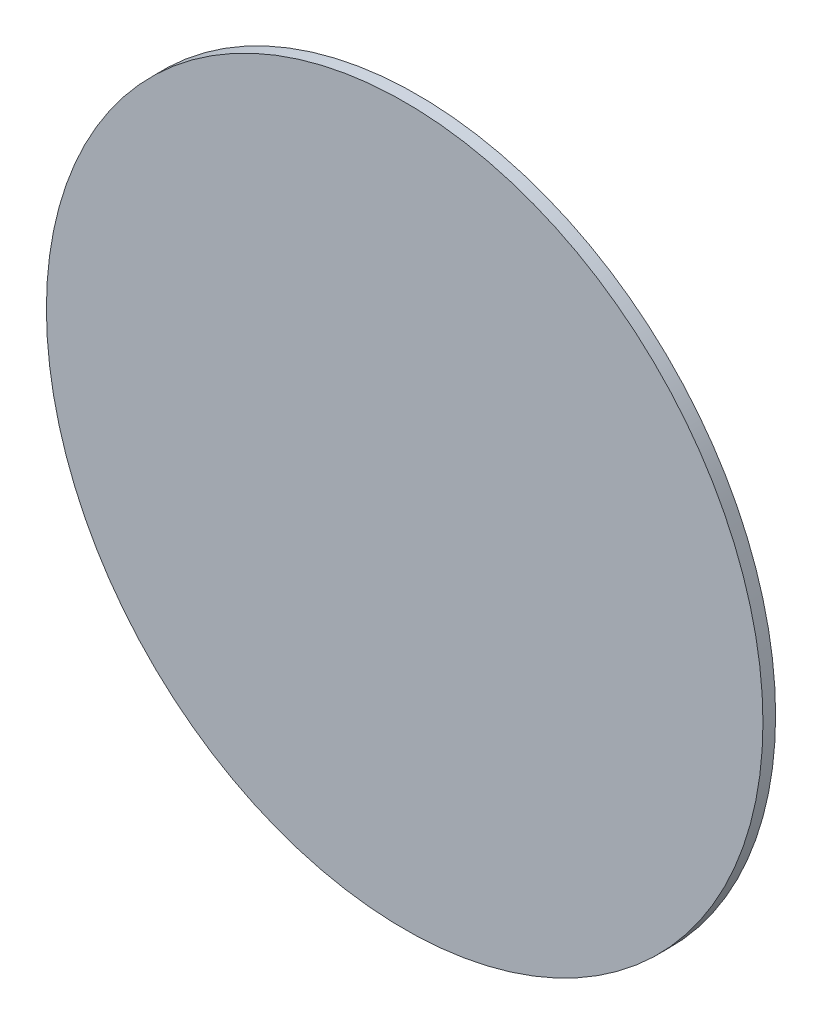
SolidWorks part; units mm, degrees
ref_plane "Front Plane" through (0, 0, 0) normal (1, 0, 0) x (0, 1, 0)
ref_plane "Top Plane" through (0, 0, 0) normal (0, 0, 1) x (0, 1, 0)
ref_plane "Right Plane" through (0, 0, 0) normal (0, 1, 0) x (-1, 0, 0)
sketch "Sketch1" plane through (0, 0, 0) normal (0, 0, 1) x (0, 1, 0)
  circle A0 centre (0, 0) radius 42.5
  dimension "D1" = 85
extrude "Boss-Extrude1" add sketch "Sketch1" along normal blind 1.5
